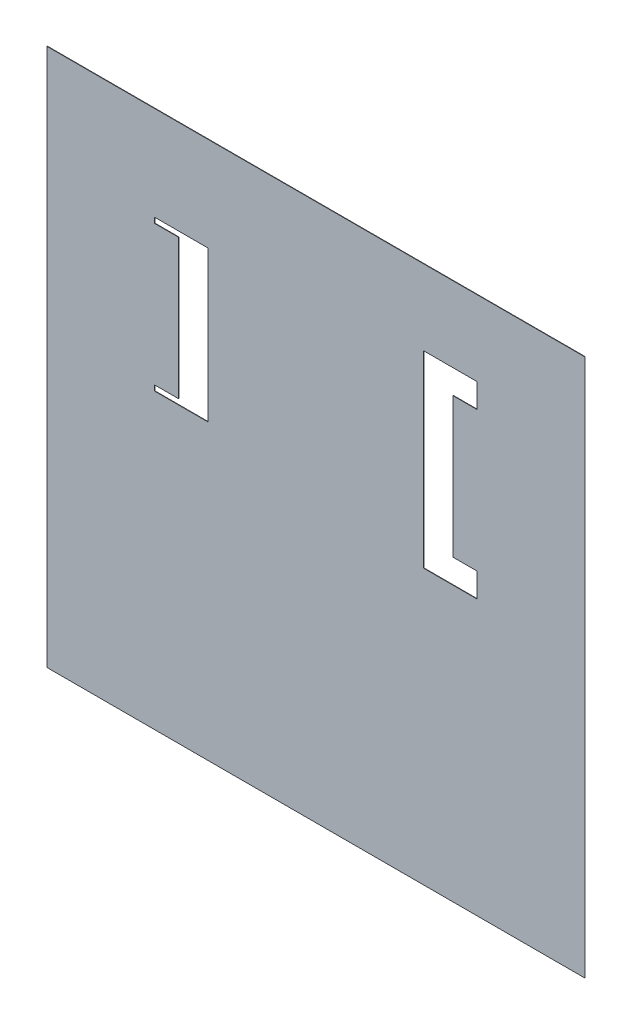
SolidWorks part; units mm, degrees
ref_plane "Front Plane" through (0, 0, 0) normal (0, 0, 1) x (1, 0, 0)
ref_plane "Top Plane" through (0, 0, 0) normal (0, 1, 0) x (1, 0, 0)
ref_plane "Right Plane" through (0, 0, 0) normal (1, 0, 0) x (0, 0, -1)
sketch "Sketch1" plane through (0, 0, 0) normal (0, 0, 1) x (1, 0, 0)
  line L1 (0, 0) -> (25.4, 0)
  line L2 (0, 0) -> (0, 25.4)
  line L3 (0, 25.4) -> (25.4, 25.4)
  line L4 (25.4, 0) -> (25.4, 25.4)
  dimension "D1" = 25.4
  dimension "D2" = 25.4
extrude "Boss-Extrude1" add sketch "Sketch1" along normal blind 0.0203
sketch "Sketch2" plane through (0, 0, 0.0203) normal (0, 0, 1) x (1, 0, 0)
  line L0 (25.4, 25.4) -> (0, 25.4) construction
  line L1 (5.08, 20.955) -> (7.62, 20.955)
  line L2 (5.08, 20.955) -> (5.08, 20.701)
  line L3 (5.08, 13.843) -> (7.62, 13.843)
  line L4 (7.62, 20.955) -> (7.62, 13.843)
  line L5 (17.78, 21.844) -> (20.32, 21.844)
  line L6 (17.78, 21.844) -> (17.78, 12.954)
  line L7 (17.78, 12.954) -> (20.32, 12.954)
  line L8 (20.32, 21.844) -> (20.32, 20.701)
  line L9 (5.08, 14.097) -> (5.08, 13.843)
  line L10 (5.08, 14.097) -> (6.223, 14.097)
  line L11 (20.32, 14.097) -> (20.32, 12.954)
  line L12 (5.08, 20.701) -> (6.223, 20.701)
  line L13 (6.223, 14.097) -> (6.223, 20.701)
  line L14 (20.32, 14.097) -> (19.177, 14.097)
  line L16 (20.32, 20.701) -> (19.177, 20.701)
  line L17 (19.177, 14.097) -> (19.177, 20.701)
  point P8 (6.35, 20.955)
  point P11 (12.7, 25.4)
  point P12 (6.35, 13.843)
  point P13 (19.05, 12.954)
  point P22 (19.177, 17.399)
  point P23 (17.78, 17.399)
  point P24 (6.223, 17.399)
  point P25 (7.62, 17.399)
  dimension "D1" = 2.54
  dimension "D2" = 2.54
  dimension "D3" = 6.35
  dimension "D4" = 12.7
  dimension "D5" = 7.112
  dimension "D6" = 8.89
  dimension "D7" = 3.556
  dimension "D8" = 4.445
  dimension "D9" = 0
  dimension "D10" = 6.604
  dimension "D11" = 1.143
  dimension "D12" = 0
  dimension "D13" = 6.604
  dimension "D14" = 1.143
extrude "Cut-Extrude8" cut sketch "Sketch2" along normal blind 3.556 and the other way through all
